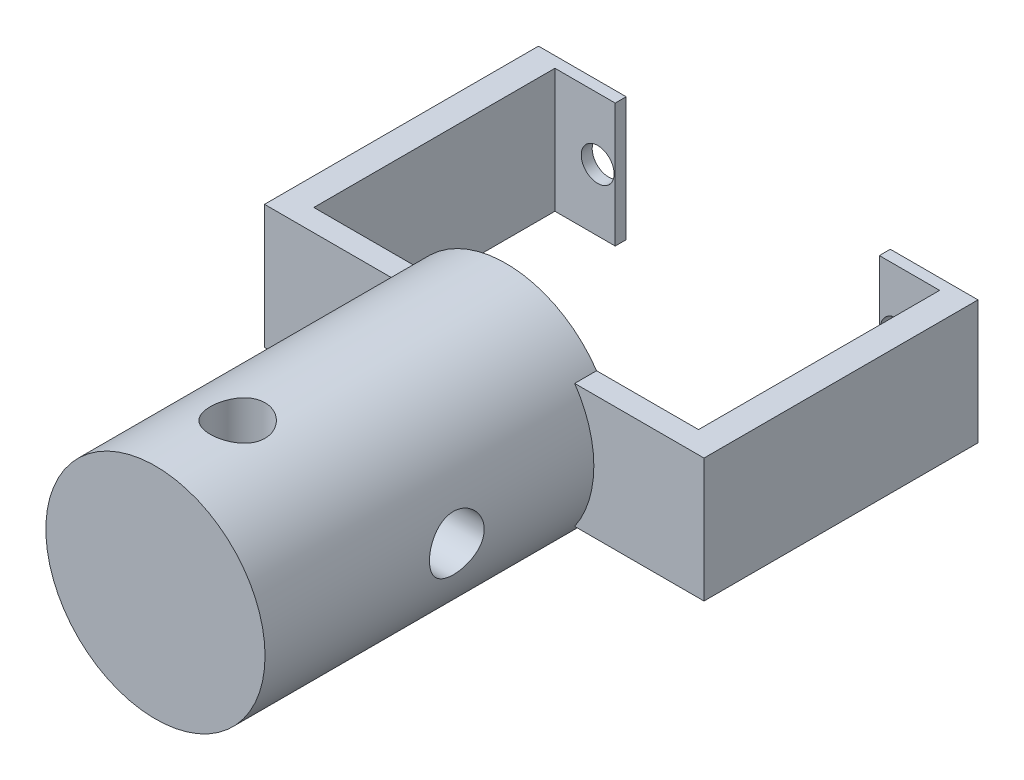
SolidWorks part; units mm, degrees
ref_plane "前视基准面" through (0, 0, 0) normal (0, 0, 1) x (1, 0, 0)
ref_plane "上视基准面" through (0, 0, 0) normal (0, 1, 0) x (1, 0, 0)
ref_plane "右视基准面" through (0, 0, 0) normal (1, 0, 0) x (0, 0, -1)
sketch "草图1" plane through (0, 0, 0) normal (0, 0, 1) x (1, 0, 0)
  line L0 (-13.65, 0) -> (13.65, 0)
  line L1 (-12.15, 0) -> (-12.05, 0)
  line L2 (-12.05, -5.65) -> (-12.05, 5.65)
  line L3 (-12.05, 5.65) -> (-16.05, 5.65)
  line L4 (-16.05, 5.65) -> (-16.05, -5.65)
  line L5 (-16.05, -5.65) -> (-12.05, -5.65)
  line L6 (-16.05, 5.65) -> (-20.05, 5.65)
  line L7 (-20.05, 5.65) -> (-20.05, -5.65)
  line L8 (-20.05, -5.65) -> (-16.05, -5.65)
  line L9 (0, -3.7751) -> (0, 5.467)
  line L10 (20.05, -5.65) -> (16.05, -5.65)
  line L11 (16.05, 5.65) -> (20.05, 5.65)
  line L12 (20.05, 5.65) -> (20.05, -5.65)
  line L13 (16.05, 5.65) -> (16.05, -5.65)
  line L14 (12.05, 5.65) -> (16.05, 5.65)
  line L15 (12.05, -5.65) -> (12.05, 5.65)
  line L16 (16.05, -5.65) -> (12.05, -5.65)
  circle A0 centre (-13.65, 0) radius 1.5
  circle A1 centre (13.65, 0) radius 1.5
  circle A2 centre (13.65, 0) radius 1.5
  point P4 (0, 0)
  point P12 (-12.05, 0)
  dimension "D2" = 3
  dimension "D3" = 3
  dimension "D1" = 27.3
  dimension "D4" = 0.1
  dimension "D5" = 11.3
  dimension "D6" = 4
  dimension "D7" = 4
extrude "凸台-拉伸1" add sketch "草图1" against normal blind 1
sketch "草图2" plane through (0, 0, 0) normal (0, 0, 1) x (1, 0, 0)
  line L0 (-20.05, -5.65) -> (-17.55, -5.65)
  line L1 (-20.05, -5.65) -> (-12.05, -5.65) construction
  line L2 (-17.55, -5.65) -> (-17.55, 5.65)
  line L3 (-12.05, 5.65) -> (-20.05, 5.65) construction
  line L4 (-17.55, 5.65) -> (-20.05, 5.65)
  line L5 (-20.05, 5.65) -> (-20.05, -5.65) construction
  line L6 (-20.05, 5.65) -> (-20.05, -5.65)
  line L7 (20.05, -5.65) -> (17.55, -5.65)
  line L8 (20.05, -5.65) -> (12.05, -5.65) construction
  line L9 (17.55, -5.65) -> (17.55, 5.65)
  line L10 (12.05, 5.65) -> (20.05, 5.65) construction
  line L11 (17.55, 5.65) -> (20.05, 5.65)
  line L12 (20.05, 5.65) -> (20.05, -5.65) construction
  line L13 (20.05, 5.65) -> (20.05, -5.65)
  dimension "D1" = 2.5
  dimension "D2" = 2.5
extrude "凸台-拉伸2" add sketch "草图2" along normal blind 22
sketch "草图3" plane through (0, 0, 22) normal (0, 0, 1) x (1, 0, 0)
  line L0 (-20.05, -5.65) -> (20.05, -5.65)
  line L1 (20.05, -5.65) -> (20.05, 5.65)
  line L2 (20.05, 5.65) -> (-20.05, 5.65)
  line L3 (-20.05, 5.65) -> (-20.05, -5.65)
extrude "凸台-拉伸3" add sketch "草图3" along normal blind 2
sketch "草图4" plane through (0, 0, 24) normal (0, 0, 1) x (1, 0, 0)
  circle A0 centre (0, 0) radius 10
  dimension "D1" = 20
extrude "凸台-拉伸4" add sketch "草图4" against normal blind 2
sketch "草图6" plane through (0, 0, 24) normal (0, 0, 1) x (1, 0, 0)
  circle A0 centre (0, 0) radius 10
extrude "凸台-拉伸5" add sketch "草图6" along normal blind 30
sketch "草图8" plane through (0, -5.65, 0) normal (0, -1, 0) x (1, 0, 0)
  line L0 (10, 54) -> (-10, 54) construction
  circle A0 centre (0, 46.5) radius 2.5
  dimension "D1" = 5
  dimension "D2" = 7.5
extrude "切除-拉伸2" cut sketch "草图8" against normal through all both and the other way through all
sketch "草图9" plane through (-20.05, 0, 0) normal (-1, 0, 0) x (0, 0, 1)
  line L0 (54, 0) -> (36.5, 0)
  line L1 (54, -10) -> (54, 10) construction
  circle A0 centre (36.5, 0) radius 2.5
  dimension "D1" = 17.5
extrude "切除-拉伸3" cut sketch "草图9" against normal through all both and the other way through all contours A0
